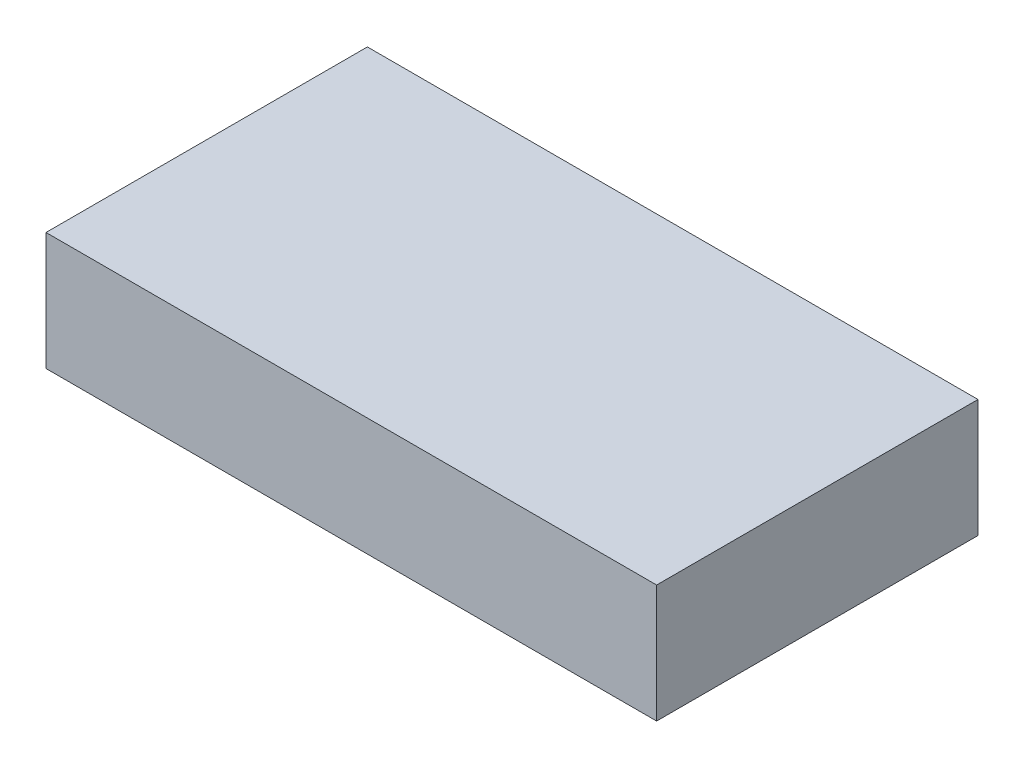
SolidWorks part; units mm, degrees
ref_plane "Front Plane" through (0, 0, 0) normal (0, 0, 1) x (1, 0, 0)
ref_plane "Top Plane" through (0, 0, 0) normal (0, 1, 0) x (1, 0, 0)
ref_plane "Right Plane" through (0, 0, 0) normal (1, 0, 0) x (0, 0, -1)
sketch "Sketch1" plane through (0, 0, 0) normal (1, 0, 0) x (0, 0, -1)
  line L1 (-15.24, 5.588) -> (15.24, 5.588)
  line L2 (-15.24, 5.588) -> (-15.24, -5.588)
  line L3 (-15.24, -5.588) -> (15.24, -5.588)
  line L4 (15.24, 5.588) -> (15.24, -5.588)
  dimension "D1" = 11.176
  dimension "D2" = 5.588
  dimension "D3" = 15.24
  dimension "D4" = 30.48
extrude "Boss-Extrude1" add sketch "Sketch1" along normal blind 57.912
